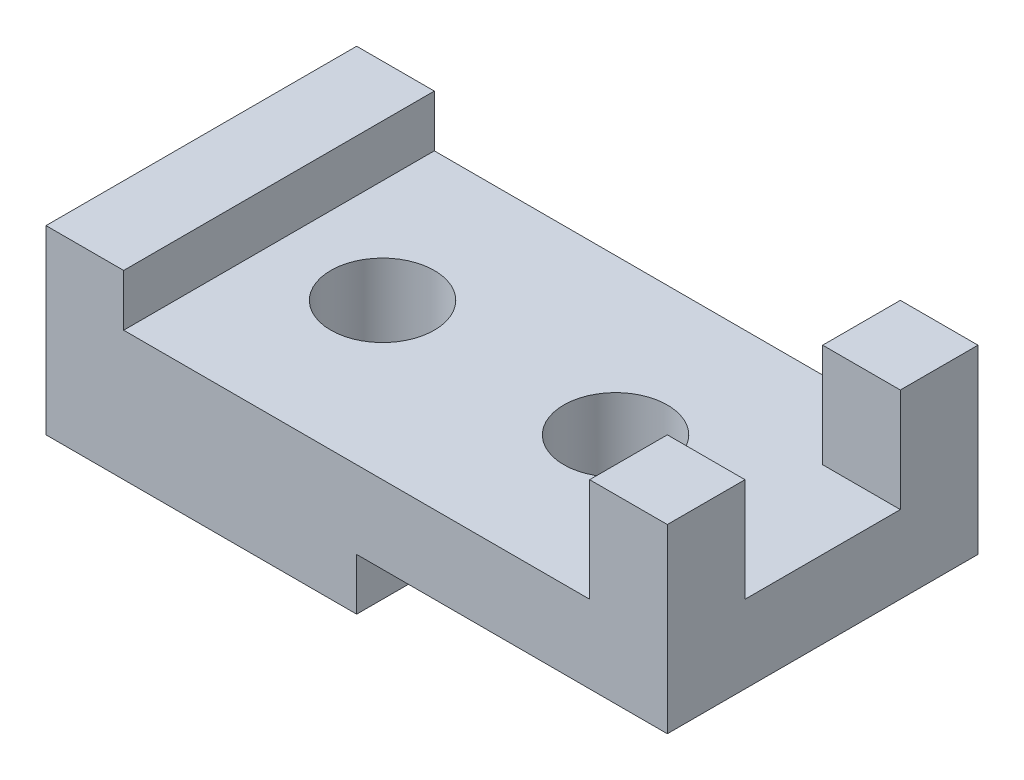
SolidWorks part; units mm, degrees
ref_plane "Front Plane" through (0, 0, 0) normal (0, 0, 1) x (1, 0, 0)
ref_plane "Top Plane" through (0, 0, 0) normal (0, 1, 0) x (1, 0, 0)
ref_plane "Right Plane" through (0, 0, 0) normal (1, 0, 0) x (0, 0, -1)
sketch "Sketch2" plane through (0, 0, 0) normal (0, 0, 1) x (1, 0, 0)
  line L1 (-60, 17.5) -> (60, 17.5)
  line L2 (-60, 17.5) -> (-60, -17.5)
  line L3 (-60, -17.5) -> (60, -17.5)
  line L4 (60, 17.5) -> (60, -17.5)
  line L5 (-60, 17.5) -> (60, -17.5) construction
  line L6 (-60, -17.5) -> (60, 17.5) construction
  point P0 (0, 0)
extrude "Boss-Extrude2" add sketch "Sketch2" along normal mid plane 60
sketch "Sketch3" plane through (0, 0, 0) normal (0, 0, 1) x (1, 0, 0)
  line L0 (60, 17.5) -> (-60, 17.5) construction
  line L1 (-45, 17.5) -> (45, 17.5)
  line L2 (-45, 17.5) -> (-45, 7.5)
  line L3 (-45, 7.5) -> (45, 7.5)
  line L4 (45, 17.5) -> (45, 7.5)
  line L6 (60, -17.5) -> (0, -17.5)
  line L7 (60, -17.5) -> (60, -7.5)
  line L8 (60, -7.5) -> (0, -7.5)
  line L9 (0, -17.5) -> (0, -7.5)
  point P6 (0, 17.5)
  dimension "D1" = 7.5
extrude "Cut-Extrude1" cut sketch "Sketch3" against normal up to next and the other way up to next
sketch "Sketch5" plane through (0, 7.5, 0) normal (0, 1, 0) x (1, 0, 0)
  line L0 (-45, -30) -> (-45, 30) construction
  line L1 (-45, -30) -> (45, -30) construction
  circle A0 centre (-25, 0) radius 10
  circle A1 centre (20, 0) radius 10
  dimension "D3" = 20
  dimension "D4" = 20
  dimension "D1" = 20
  dimension "D2" = 45
  dimension "D5" = 30
  dimension "D6" = 30
extrude "Cut-Extrude3" cut sketch "Sketch5" against normal up to next
sketch "Sketch6" plane through (0, 17.5, 0) normal (0, 1, 0) x (1, 0, 0)
  line L1 (60, 30) -> (45, 30)
  line L2 (60, 30) -> (60, -30)
  line L3 (60, -30) -> (45, -30)
  line L4 (45, 30) -> (45, -30)
extrude "Boss-Extrude3" add sketch "Sketch6" along normal blind 10
sketch "Sketch7" plane through (60, 0, 0) normal (1, 0, 0) x (0, 0, -1)
  line L0 (-30, 27.5) -> (30, 27.5) construction
  line L1 (-15, 27.5) -> (15, 27.5)
  line L2 (-15, 27.5) -> (-15, 7.5)
  line L3 (-15, 7.5) -> (15, 7.5)
  line L4 (15, 27.5) -> (15, 7.5)
  point P6 (0, 27.5)
extrude "Cut-Extrude4" cut sketch "Sketch7" against normal up to next
